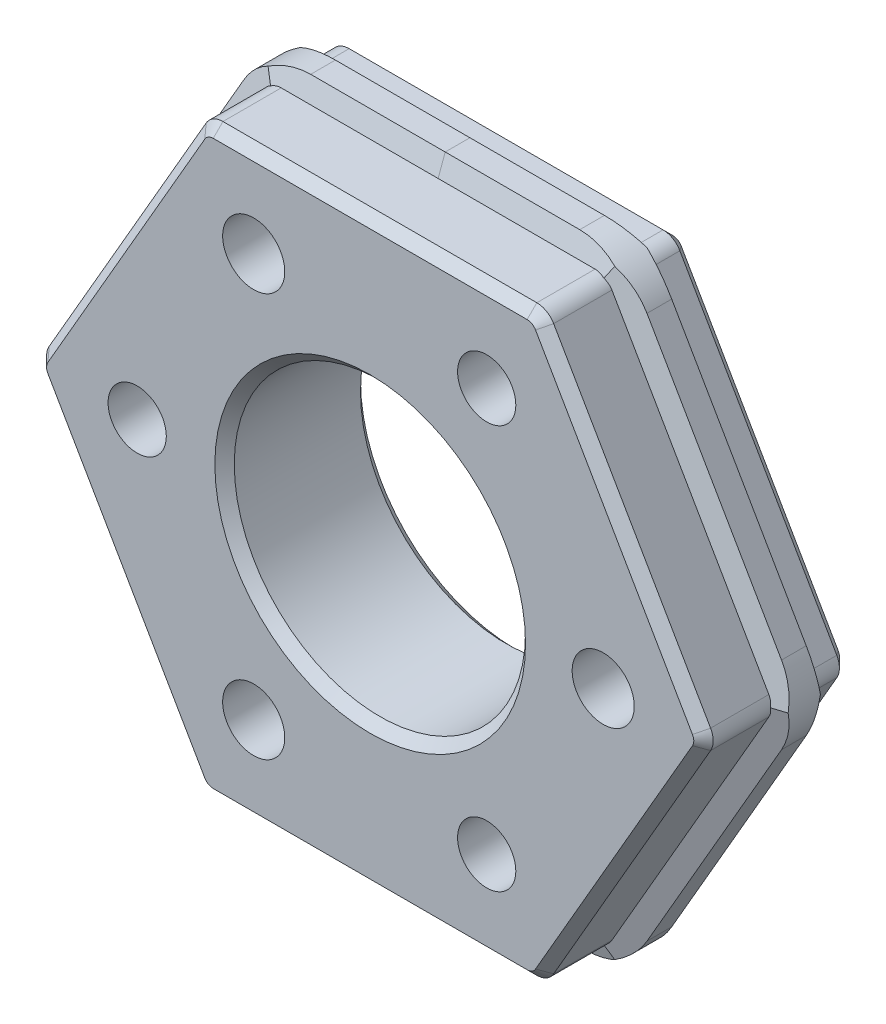
SolidWorks part; units mm, degrees
material "6061 合金"
ref_plane "前视基准面" through (0, 0, 0) normal (0, 0, 1) x (1, 0, 0)
ref_plane "上视基准面" through (0, 0, 0) normal (0, 1, 0) x (1, 0, 0)
ref_plane "右视基准面" through (0, 0, 0) normal (1, 0, 0) x (0, 0, -1)
other "Configuration Table"
sketch "草图1" plane through (0, 0, 0) normal (0, 0, 1) x (1, 0, 0)
  line L1 (-20, 20) -> (20, 20)
  line L2 (-20, 20) -> (-20, -20)
  line L3 (-20, -20) -> (20, -20)
  line L4 (20, 20) -> (20, -20)
  line L5 (0, -20) -> (0, 20) construction
  line L6 (-20, 0) -> (20, 0) construction
  circle A0 centre (0, 0) radius 7.5
  circle A1 centre (0, 0) radius 18 construction
  circle A2 centre (0, 0) radius 12 construction
  dimension "D1" = 36
  dimension "D2" = 15
  dimension "D3" = 24
  dimension "D7" = 40
extrude "凸台-拉伸1" add sketch "草图1" along normal mid plane 6
sketch "草图23" plane through (0, 0, 3) normal (0, 0, 1) x (1, 0, 0)
  line L0 (20, 20) -> (20, -20)
  line L8 (-20, -20) -> (20, -20)
  line L11 (20, -20) -> (20, 20)
  line L12 (20, -20) -> (20, 20)
  line L14 (20, 20) -> (-20, 20)
  line L15 (-20, 20) -> (-20, -20)
  line L16 (-20, -20) -> (20, -20)
  line L22 (20, 20) -> (-20, 20)
  line L23 (-20, 20) -> (-20, -20)
  line M23 (-20, -20) -> (20, -20)
  line M25 (20, -20) -> (20, 20)
  line M35 (20, 20) -> (-20, 20)
  line M37 (-20, 20) -> (-20, -20)
  circle M39 centre (0, 0) radius 7.5
  dimension "D1" = 0
extrude "凸台-拉伸4" add sketch "草图23" along normal blind 1.5 contours M23 M25 M35 M37 M39
sketch "草图8" plane through (0, 0, -3) normal (0, 0, -1) x (-1, 0, 0)
  circle A0 centre (0, 0) radius 12 construction
  point P0 (-12, 0)
  point P1 (6, 10.3923)
  point P9 (6, -10.3923)
  dimension "D1" = 24
  dimension "D2" = 3
hole_wizard "M3 六角圆柱头螺钉的柱形沉头孔1" positions "草图8" profile "草图9" counterbore size "M3" standard "GB" end condition through all
sketch "草图9" plane through (12, 0, -3) normal (1, 0, 0) x (0, 1, 0)
  line L0 (0, 0) -> (0, 7.5)
  line L1 (0, 7.5) -> (1.6, 7.5)
  line L3 (1.6, 7.5) -> (1.6, 4)
  line L4 (1.6, 4) -> (3, 4)
  line L5 (3, 4) -> (3, 0)
  line L7 (3, 0) -> (0, 0)
  line L11 (0, -6.35) -> (0, 107.95) construction
  dimension "通孔孔直径" = 3.2
  dimension "通孔孔深度" = 7.5
  dimension "柱形沉头孔直径" = 6
  dimension "柱形沉头孔深度" = 4
sketch "草图24" plane through (0, 0, 4.5) normal (0, 0, 1) x (1, 0, 0)
  circle A0 centre (0, 0) radius 12 construction
  point P0 (-12, 0)
  point P13 (6, 10.3923)
  point P14 (6, -10.3923)
  dimension "D1" = 24
  dimension "D2" = 3
hole_wizard "Ø3.0mm 暗销孔1" positions "草图24" profile "草图25" hole size "Ø3.0" standard "BSI"
sketch "草图25" plane through (-12, 0, 4.5) normal (1, 0, 0) x (0, -1, 0)
  line L0 (0, 0) -> (0, 4.9013)
  line L1 (0, 4.9013) -> (1.5, 4)
  line L2 (1.5, 4) -> (1.5, 0)
  line L5 (1.5, 0) -> (0, 0)
  line L10 (0, 4.9013) -> (-1.5, 4) construction
  line L11 (0, -6.35) -> (0, 107.95) construction
  dimension "孔直径" = 3
  dimension "孔深度" = 4
  dimension "导头角度" = 118
ref_plane "基准面1" through (0, 0, 0) normal (0, 0, -1) x (-1, 0, 0)
sketch "草图26" plane through (0, 0, -3) normal (0, 0, -1) x (-1, 0, 0)
  line L1 (-17.3205, 0) -> (-8.6603, -15)
  line L2 (-8.6603, -15) -> (8.6603, -15)
  line L3 (8.6603, -15) -> (17.3205, 0)
  line L4 (17.3205, 0) -> (8.6603, 15)
  line L5 (8.6603, 15) -> (-8.6603, 15)
  line L6 (-8.6603, 15) -> (-17.3205, 0)
  circle A1 centre (0, 0) radius 15 construction
  point P1 (0, 0)
  dimension "D1" = 30
extrude "切除-拉伸1" cut sketch "草图26" against normal through all flip side to cut
sketch "草图43" plane through (0, 0, 0) normal (1, 0, 0) x (0, 0, -1)
  line L1 (-1, 15) -> (1, 15)
  line L3 (1, 15) -> (0.636, 16)
  line L4 (0.636, 16) -> (-0.636, 16)
  line L5 (-0.636, 16) -> (-1, 15)
  line L7 (-4.5, 15) -> (3, 15) construction
  line L9 (0, 22.7244) -> (0, -9.6288) construction
  point P4 (0, 0)
  point P5 (-1, 15)
  point P6 (-1, 14.7058)
  point P7 (-1, 15)
  point P10 (0, 0)
  dimension "D1" = 2
  dimension "D2" = 40
  dimension "D3" = 1
ref_plane "基准面3" through (0, 0, -1) normal (0, 0, -1) x (-1, 0, 0)
sketch "草图44" plane through (0, 0, -1) normal (0, 0, -1) x (-1, 0, 0)
  line L4 (-17.3205, 0) -> (-8.6603, -15)
  line L25 (-17.3205, 0) -> (-8.6603, -15)
  line L34 (-8.6603, -15) -> (8.6603, -15)
  line L36 (-8.6603, -15) -> (8.6603, -15)
  line L38 (8.6603, -15) -> (17.3205, 0)
  line L40 (8.6603, -15) -> (17.3205, 0)
  line L42 (17.3205, 0) -> (8.6603, 15)
  line L43 (17.3205, 0) -> (8.6603, 15)
  line L44 (8.6603, 15) -> (-8.6603, 15)
  line L45 (8.6603, 15) -> (-8.6603, 15)
  line L46 (-8.6603, 15) -> (-17.3205, 0)
  line L47 (-8.6603, 15) -> (-17.3205, 0)
  dimension "D1" = 0
sweep "扫描1" add profiles "草图43" path "草图44"
fillet "圆角2" radius 4 6 edges at (9.2376, 16, 0) (-9.2376, 16, 0) (-18.4752, 0, 0) (-9.2376, -16, 0) (9.2376, -16, 0) (18.4752, 0, 0)
fillet "圆角3" radius 1 12 edges at (-8.6603, 15, -2) (-8.6603, 15, 2.75) (-17.3205, 0, -2) (-17.3205, 0, 2.75) (-8.6603, -15, 2.75) (-8.6603, -15, -2) (8.6603, -15, 2.75) (8.6603, -15, -2) (17.3205, 0, -2) (17.3205, 0, 2.75) (8.6603, 15, 2.75) (8.6603, 15, -2)
chamfer "倒角1" distance 0.5 angle 45 26 edges at (7.5, 0, 4.5) (7.5, 0, -3) (0, -15, -3) (-8.5829, -14.866, -3) (8.5829, -14.866, -3) (-12.9904, -7.5, -3) (12.9904, -7.5, -3) (-17.1658, 0, -3) (17.1658, 0, -3) (-12.9904, 7.5, -3) (12.9904, 7.5, -3) (-8.5829, 14.866, -3) (8.5829, 14.866, -3) (0, 15, -3) (0, -15, 4.5) (-8.5829, -14.866, 4.5) (8.5829, -14.866, 4.5) (-12.9904, -7.5, 4.5) (12.9904, -7.5, 4.5) (-17.1658, 0, 4.5) (17.1658, 0, 4.5) (-12.9904, 7.5, 4.5) (12.9904, 7.5, 4.5) (-8.5829, 14.866, 4.5) (8.5829, 14.866, 4.5) (0, 15, 4.5)
